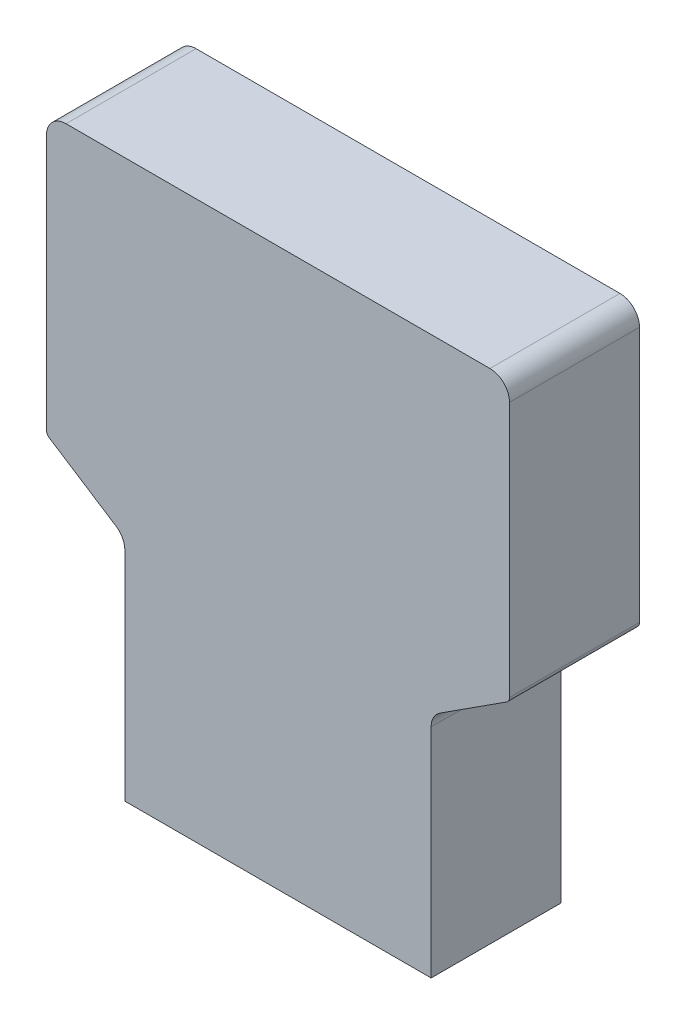
SolidWorks part; units mm, degrees
ref_plane "Front Plane" through (0, 0, 0) normal (0, 0, 1) x (1, 0, 0)
ref_plane "Top Plane" through (0, 0, 0) normal (0, 1, 0) x (1, 0, 0)
ref_plane "Right Plane" through (0, 0, 0) normal (1, 0, 0) x (0, 0, -1)
sketch "Sketch1" plane through (0, 0, 0) normal (0, 0, 1) x (1, 0, 0)
  line L0 (-26.7827, -38.7991) -> (-26.7827, -5.4343)
  line L1 (-26.7827, -38.7991) -> (20.2173, -38.7991)
  line L2 (-38.8027, 4.496) -> (-38.8027, 43.7009)
  line L3 (-35.8027, 46.7009) -> (29.2373, 46.7009)
  line L4 (32.2373, 4.496) -> (32.2373, 43.7009)
  line L5 (-26.7827, -38.7991) -> (32.2373, 46.7009) construction
  line L6 (-38.8027, 46.7009) -> (32.2373, -38.7991) construction
  line L7 (-28.1571, -2.913) -> (-38.3446, 3.6555)
  line L8 (20.2173, -38.7991) -> (20.2173, -5.4343)
  line L9 (21.5916, -2.913) -> (31.7792, 3.6555)
  line L10 (-3.2827, 3.9509) -> (-3.2827, -38.7991) construction
  arc A0 (-38.8027, 43.7009) -> (-35.8027, 46.7009) centre (-35.8027, 43.7009) cw
  arc A1 (29.2373, 46.7009) -> (32.2373, 43.7009) centre (29.2373, 43.7009) cw
  arc A2 (31.7792, 3.6555) -> (32.2373, 4.496) centre (31.2373, 4.496) ccw
  arc A3 (-38.3446, 3.6555) -> (-38.8027, 4.496) centre (-37.8027, 4.496) cw
  arc A4 (-26.7827, -5.4343) -> (-28.1571, -2.913) centre (-29.7827, -5.4343) ccw
  arc A5 (20.2173, -5.4343) -> (21.5916, -2.913) centre (23.2173, -5.4343) cw
  point P1 (0, 0)
  point P14 (23.5, -8.9241)
  point P15 (0, 0)
  point P24 (32.2373, 3.9509)
  point P27 (-38.8027, 3.9509)
  point P30 (-26.7827, -3.7991)
  point P33 (20.2173, -3.7991)
  point P34 (0, 0)
  point P35 (-3.2827, 4.496)
  point P36 (-3.2827, 4.496)
  dimension "D11" = 3
  dimension "D12" = 1
  dimension "D13" = 3
  dimension "D1" = 85.5
  dimension "D2" = 59.02
  dimension "D3" = 23.5
  dimension "D4" = 47
  dimension "D5" = 35
  dimension "D6" = 35
  dimension "D7" = 71.04
  dimension "D8" = 42.75
  dimension "D9" = 85.5
  dimension "D10" = 42.75
extrude "Boss-Extrude1" add sketch "Sketch1" along normal mid plane 19.95 contours L8 A5 L9 A2 L4 A1 L3 A0 L2 A3 L7 A4 L0 L1
sketch "Sketch4" plane through (0, 0, 9.975) normal (0, 0, 1) x (1, 0, 0)
  line L0 (-25.2827, -38.7991) -> (-25.2827, 46.7009)
  line L1 (-26.7827, -38.7991) -> (20.2173, -38.7991) construction
  line L2 (-35.8027, 46.7009) -> (29.2373, 46.7009) construction
  line L3 (18.7173, -38.7991) -> (18.7173, 46.7009)
  line L4 (-3.2827, -38.7991) -> (-3.2827, -17.9976) construction
  dimension "D1" = 44
  dimension "D2" = 22
